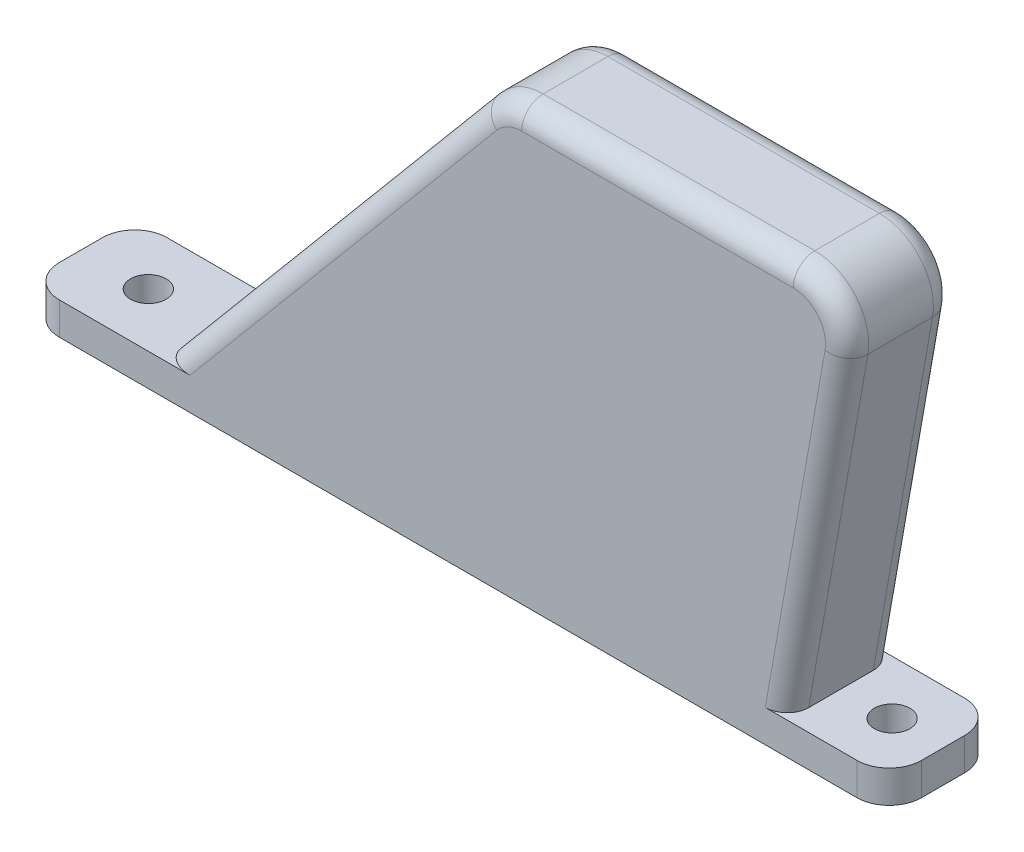
SolidWorks part; units mm, degrees
ref_plane "Front Plane" through (0, 0, 0) normal (0, 0, 1) x (1, 0, 0)
ref_plane "Top Plane" through (0, 0, 0) normal (0, 1, 0) x (1, 0, 0)
ref_plane "Right Plane" through (0, 0, 0) normal (1, 0, 0) x (0, 0, -1)
sketch "Sketch1" plane through (0, 0, 0) normal (0, 0, 1) x (1, 0, 0)
  line L0 (0, 0) -> (60, 0)
  line L1 (60, 0) -> (67.0531, 40)
  line L14 (0, 0) -> (33.564, 40)
  line L15 (33.564, 40) -> (67.0531, 40)
  point P3 (83.7419, 38.1461)
  point P6 (80.3796, 40)
  dimension "D2" = 50
  dimension "D1" = 60
  dimension "D3" = 40
  dimension "D4" = 80
extrude "Boss-Extrude1" add sketch "Sketch1" along normal blind 10
sketch "Sketch2" plane through (0, 0, 0) normal (0, -1, 0) x (1, 0, 0)
  line L0 (0, 10) -> (-10, 10)
  line L9 (-10, 10) -> (-10, 0)
  line L10 (-10, 0) -> (0, 0)
  line L13 (70, 0) -> (70, 10)
  line L14 (70, 10) -> (60, 10)
  line L16 (60, 10) -> (0, 10)
  line L17 (60, 10) -> (60, 0) construction
  line L18 (0, 0) -> (70, 0)
extrude "Boss-Extrude2" add sketch "Sketch2" against normal blind 3
fillet "Fillet2" radius 3 4 edges at (-10, 1.5, 0) (70, 1.5, 10) (70, 1.5, 0) (-10, 1.5, 10)
sketch "Sketch3" plane through (0, 3, 0) normal (0, 1, 0) x (1, 0, 0)
  line L0 (-10, -5) -> (2.5173, -5) construction
  line L1 (-10, -7) -> (-10, -3) construction
  line L2 (2.5173, -10) -> (2.5173, 0) construction
  line L3 (60.529, -5) -> (70, -5) construction
  line L5 (70, -3) -> (70, -7) construction
  line L6 (60.529, 0) -> (60.529, -10) construction
  circle A0 centre (65.2645, -5) radius 1.65
  circle A1 centre (-3.7414, -5) radius 1.65
  point P8 (73.277, -5)
  point P9 (75.6787, -5)
  point P16 (0, 0)
  dimension "D1" = 3.3
extrude "Cut-Extrude2" cut sketch "Sketch3" against normal through all
fillet "Fillet4" radius 5 2 edges at (67.0531, 40, 5) (33.564, 40, 5)
fillet "Fillet3" radius 2 10 edges at (63.2737, 18.5659, 0) (63.2737, 18.5659, 10) (17.2913, 20.607, 10) (17.2913, 20.607, 0) (64.9245, 38.2139, 10) (64.9245, 38.2139, 0) (48.4949, 40, 10) (48.4949, 40, 0) (33.7824, 39.5315, 10) (33.7824, 39.5315, 0)
